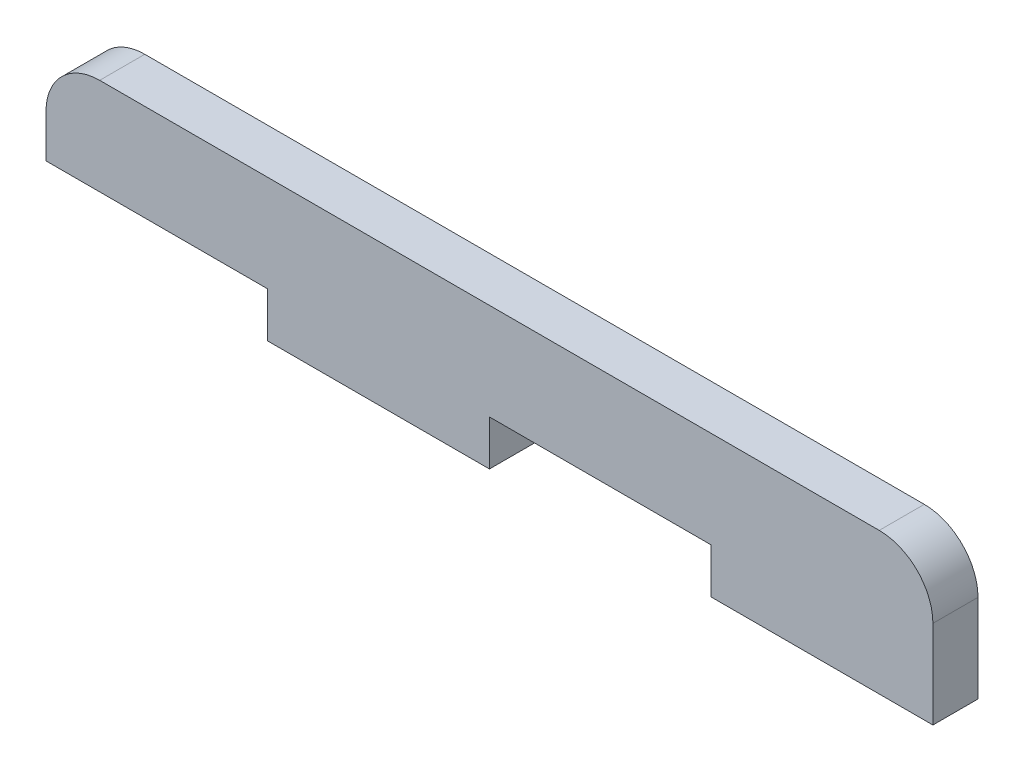
SolidWorks part; units mm, degrees
ref_plane "Front Plane" through (0, 0, 0) normal (0, 0, 1) x (1, 0, 0)
ref_plane "Top Plane" through (0, 0, 0) normal (0, 1, 0) x (1, 0, 0)
ref_plane "Right Plane" through (0, 0, 0) normal (1, 0, 0) x (0, 0, -1)
other "Center of Mass"
sketch "Sketch1" plane through (0, 0, 0) normal (0, 0, 1) x (1, 0, 0)
  line L1 (-57.0553, 7.6125) -> (47.8467, 7.6125)
  line L2 (-57.0553, 7.6125) -> (-57.0553, -9.1515)
  line L3 (-57.0553, -9.1515) -> (47.8467, -9.1515)
  line L4 (47.8467, 7.6125) -> (47.8467, -9.1515)
  dimension "D1" = 104.902
  dimension "D2" = 16.764
extrude "Boss-Extrude1" add sketch "Sketch1" along normal blind 5.334
sketch "Sketch2" plane through (0, 0, 5.334) normal (0, 0, 1) x (1, 0, 0)
  line L0 (-57.0553, -9.1515) -> (47.8467, -9.1515) construction
  line L1 (-57.0553, -9.1515) -> (-30.8298, -9.1515)
  line L2 (-57.0553, -9.1515) -> (-57.0553, -3.8175)
  line L3 (-57.0553, -3.8175) -> (-30.8298, -3.8175)
  line L4 (-30.8298, -9.1515) -> (-30.8298, -3.8175)
  line L5 (-4.6043, -9.1515) -> (21.6212, -9.1515)
  line L6 (-4.6043, -9.1515) -> (-4.6043, -3.8175)
  line L7 (-4.6043, -3.8175) -> (21.6212, -3.8175)
  line L8 (21.6212, -9.1515) -> (21.6212, -3.8175)
  line L9 (-30.8298, -3.8175) -> (-4.6043, -3.8175) construction
  line L10 (21.6212, -3.8175) -> (47.8467, -3.8175) construction
  line L11 (47.8467, -9.1515) -> (47.8467, 7.6125) construction
  dimension "D1" = 5.334
extrude "Cut-Extrude1" cut sketch "Sketch2" against normal through all
fillet "Fillet1" radius 6.35 2 edges at (47.8467, 7.6125, 2.667) (-57.0553, 7.6125, 2.667)
equation "\"MDF\"= .21in"
equation "\"Foamcore\"= .13in"
equation "\"Gmaterial\"= \"MDF\""
equation "\"D2@Sketch1\"=\"MDF\"+.45"
equation "\"D1@Boss-Extrude1\"=\"MDF\""
equation "\"D1@Sketch2\"=\"MDF\""
